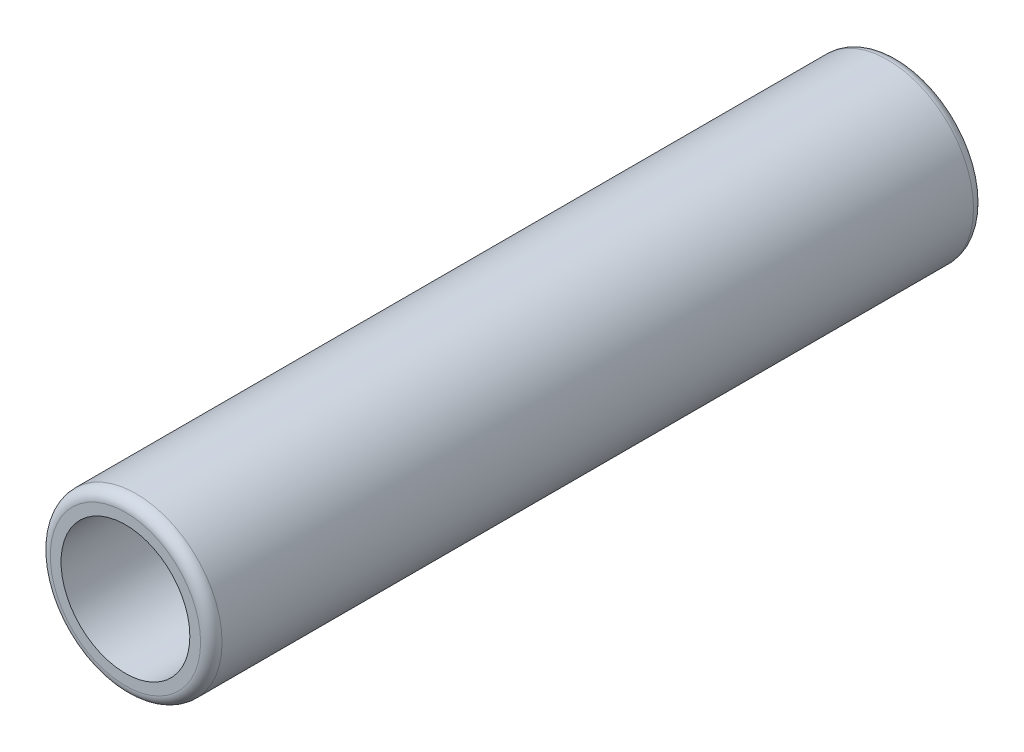
SolidWorks part; units mm, degrees
material "Простая углеродистая сталь"
ref_plane "Спереди" through (0, 0, 0) normal (0, 0, 1) x (1, 0, 0)
ref_plane "Сверху" through (0, 0, 0) normal (0, 1, 0) x (1, 0, 0)
ref_plane "Справа" through (0, 0, 0) normal (1, 0, 0) x (0, 0, -1)
sketch "Эскиз1" plane through (0, 0, 0) normal (0, 0, 1) x (1, 0, 0)
  circle A0 centre (0, 0) radius 4
  circle A1 centre (0, 0) radius 3
  dimension "D1" = 6
  dimension "D2" = 8
extrude "Бобышка-Вытянуть1" add sketch "Эскиз1" along normal blind 36
cosmetic thread "Условное изображение резьбы1" parameters "D2"=18
fillet "Скругление1" radius 0.5 2 edges at (4, 0, 0) (4, 0, 36)
